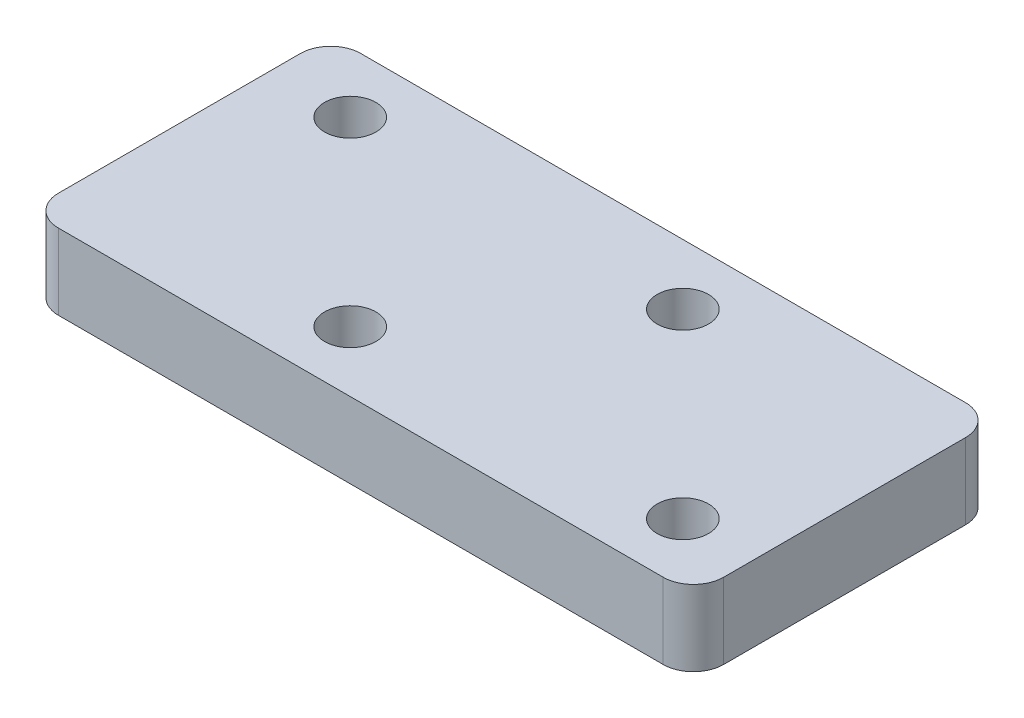
SolidWorks part; units mm, degrees
ref_plane "前视基准面" through (0, 0, 0) normal (0, 0, 1) x (1, 0, 0)
ref_plane "上视基准面" through (0, 0, 0) normal (0, 1, 0) x (1, 0, 0)
ref_plane "右视基准面" through (0, 0, 0) normal (1, 0, 0) x (0, 0, -1)
sketch "草图1" plane through (0, 0, 0) normal (0, 1, 0) x (1, 0, 0)
  line L0 (5.3, 16) -> (27.3, 16) construction
  line L1 (0, 0) -> (44, 0)
  line L2 (0, 0) -> (0, 20)
  line L3 (0, 20) -> (44, 20)
  line L4 (44, 0) -> (44, 20)
  circle A0 centre (5.3, 16) radius 1.7
  circle A1 centre (17.3, 4) radius 1.7
  circle A2 centre (27.3, 16) radius 1.7
  circle A3 centre (39.3, 4) radius 1.7
  dimension "D1" = 3.4
  dimension "D2" = 5.3
  dimension "D4" = 12
  dimension "D5" = 4
  dimension "D6" = 12
  dimension "D3" = 20
  dimension "D7" = 44
  dimension "D9" = 22
  dimension "D8" = 2
extrude "凸台-拉伸1" add sketch "草图1" along normal blind 5
fillet "圆角1" radius 2 4 edges at (44, 2.5, -20) (44, 2.5, 0) (0, 2.5, 0) (0, 2.5, -20)
